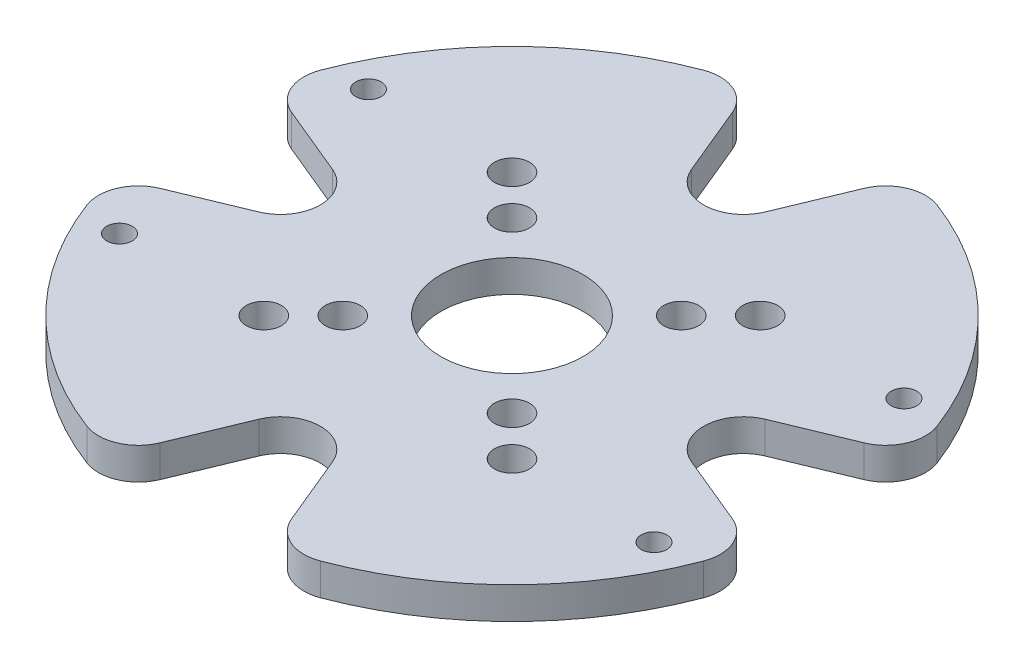
SolidWorks part; units mm, degrees
ref_plane "Front Plane" through (0, 0, 0) normal (0, 0, 1) x (1, 0, 0)
ref_plane "Top Plane" through (0, 0, 0) normal (0, 1, 0) x (1, 0, 0)
ref_plane "Right Plane" through (0, 0, 0) normal (1, 0, 0) x (0, 0, -1)
sketch "Sketch1" plane through (0, 0, 0) normal (0, 1, 0) x (1, 0, 0)
  circle A0 centre (-26.0147, -1.0931) radius 41.3322
  circle A1 centre (-59.5815, 14.4786) radius 1.6
  circle A2 centre (-59.5196, -16.7975) radius 1.6
  circle A3 centre (7.4901, -16.7975) radius 1.6
  circle A4 centre (7.552, 14.4786) radius 1.6
  dimension "D1" = 3.2
  dimension "D2" = 82.6645
  dimension "D3" = 7.4901
  dimension "D4" = 7.552
  dimension "D5" = 26.0147
  dimension "D6" = 59.5196
  dimension "D7" = 59.5815
  dimension "D8" = 14.4786
  dimension "D9" = 1.0931
  dimension "D10" = 16.7975
extrude "Boss-Extrude1" add sketch "Sketch1" along normal blind 4
sketch "Sketch2" plane through (0, 4, 0) normal (0, 1, 0) x (1, 0, 0)
  circle A0 centre (-26.0147, -1.0931) radius 8.913
  circle A1 centre (-26.0147, -1.0931) radius 15 construction
  circle A2 centre (-26.0147, -1.0931) radius 22 construction
  circle A3 centre (-26.0147, -1.0931) radius 31.5 construction
  circle A4 centre (-15.4081, 9.5135) radius 2.2
  circle A5 centre (-10.4584, 14.4633) radius 2.2
  circle A6 centre (-36.6213, 9.5135) radius 2.2
  circle A7 centre (-41.5711, 14.4633) radius 2.2
  circle A8 centre (-36.6213, -11.6997) radius 2.2
  circle A9 centre (-41.5711, -16.6494) radius 2.2
  circle A10 centre (-15.4081, -11.6997) radius 2.2
  circle A11 centre (-10.4584, -16.6494) radius 2.2
  point P0 (-26.0147, -1.0931)
extrude "Cut-Extrude1" cut sketch "Sketch2" against normal blind 12
sketch "Sketch4" plane through (0, 4, 0) normal (0, 1, 0) x (1, 0, 0)
  line L0 (-66.119, 8.9069) -> (-41.9769, -1.0931)
  line L1 (-41.9769, -1.0931) -> (-66.119, -11.0931)
  line L2 (-67.347, -1.0931) -> (-41.9769, -1.0931) construction
  circle A0 centre (-26.0147, -1.0931) radius 41.3322 construction
  circle A1 centre (-26.0147, -1.0931) radius 41.3322 construction
  arc A2 (-66.119, 8.9069) -> (-66.119, -11.0931) centre (-26.0147, -1.0931) ccw
  dimension "D1" = 45
  dimension "D2" = 20
extrude "Cut-Extrude2" cut sketch "Sketch4" against normal blind 12 contours L0 L1 A2
fillet "Fillet1" radius 5 3 edges at (-66.119, 2, 11.0931) (-41.9769, 2, 1.0931) (-66.119, 2, -8.9069)
pattern_circular "CirPattern1" count 4 over 360 about axis through (-26.0147, 0, 1.0931) along (0, 1, 0) of "Fillet1", "Cut-Extrude2"
